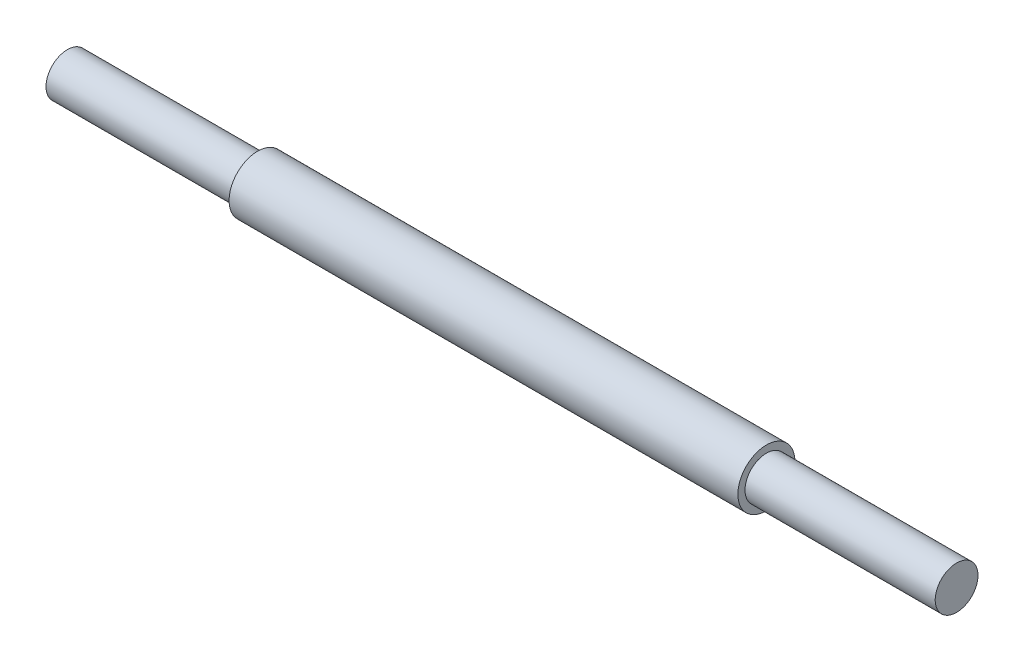
SolidWorks part; units mm, degrees
ref_plane "Plan de face" through (0, 0, 0) normal (0, 0, 1) x (1, 0, 0)
ref_plane "Plan de dessus" through (0, 0, 0) normal (0, 1, 0) x (1, 0, 0)
ref_plane "Plan de droite" through (0, 0, 0) normal (1, 0, 0) x (0, 0, -1)
sketch "Esquisse1" plane through (0, 0, 0) normal (1, 0, 0) x (0, 0, -1)
  circle A0 centre (-11.8661, 7.686) radius 12
extrude "Boss.-Extru.1" add sketch "Esquisse1" along normal blind 214
sketch "Esquisse2" plane through (214, 0, 0) normal (1, 0, 0) x (0, 0, -1)
  circle A0 centre (-11.8661, 7.686) radius 9
extrude "Boss.-Extru.2" add sketch "Esquisse2" along normal blind 80
sketch "Esquisse3" plane through (0, 0, 0) normal (-1, 0, 0) x (0, 0, 1)
  circle A0 centre (11.8661, 7.686) radius 9
extrude "Boss.-Extru.3" add sketch "Esquisse3" along normal blind 80
